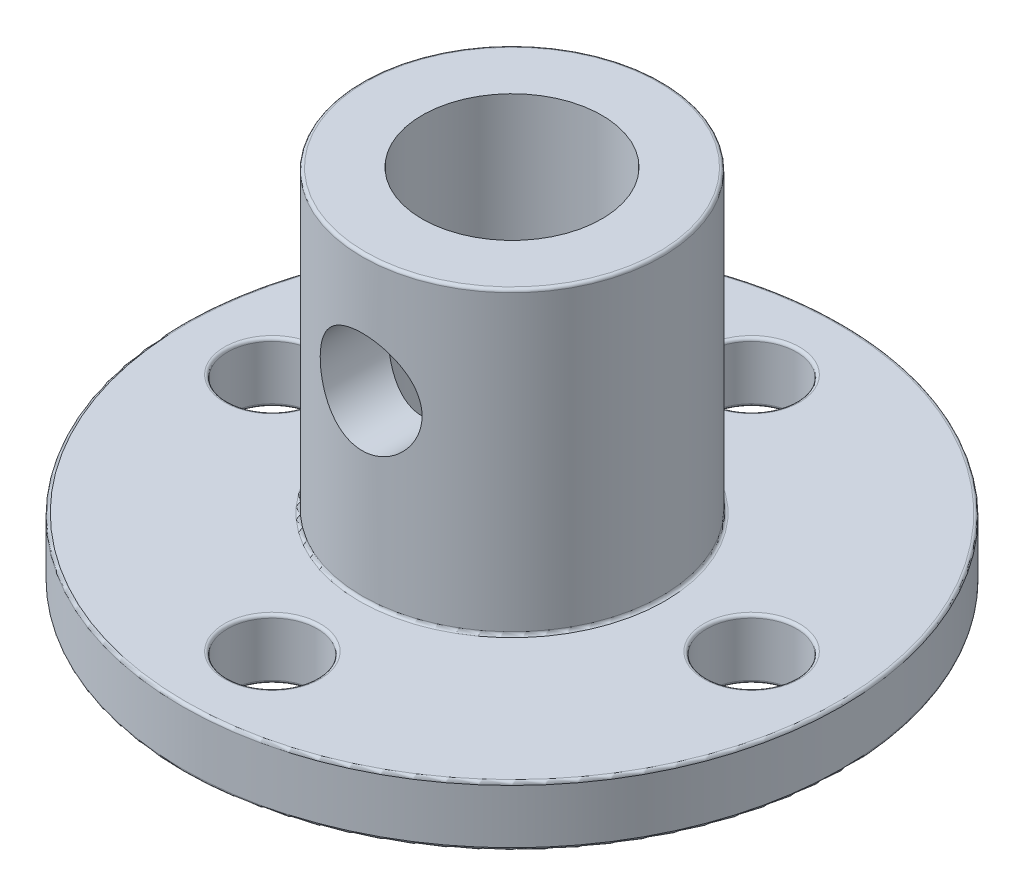
SolidWorks part; units mm, degrees
ref_plane "Front Plane" through (0, 0, 0) normal (0, 0, 1) x (1, 0, 0)
ref_plane "Top Plane" through (0, 0, 0) normal (0, 1, 0) x (1, 0, 0)
ref_plane "Right Plane" through (0, 0, 0) normal (1, 0, 0) x (0, 0, -1)
sketch "Sketch2" plane through (0, 0, 0) normal (0, 1, 0) x (1, 0, 0)
  circle A0 centre (0, 0) radius 11
  dimension "D1" = 22
extrude "Boss-Extrude1" add sketch "Sketch2" along normal blind 2
sketch "Sketch3" plane through (0, 2, 0) normal (0, 1, 0) x (1, 0, 0)
  circle A0 centre (0, 0) radius 5
  dimension "D1" = 10
extrude "Boss-Extrude2" add sketch "Sketch3" along normal blind 10
sketch "Sketch4" plane through (0, 12, 0) normal (0, 1, 0) x (1, 0, 0)
  circle A0 centre (0, 0) radius 3
  dimension "D1" = 6
extrude "Cut-Extrude1" cut sketch "Sketch4" against normal through all
sketch "Sketch5" plane through (0, 2, 0) normal (0, 1, 0) x (1, 0, 0)
  circle A0 centre (0, 0) radius 8 construction
  circle A1 centre (0, -8) radius 1.5
  circle A2 centre (-8, 0) radius 1.5
  circle A3 centre (0, 8) radius 1.5
  circle A4 centre (8, 0) radius 1.5
  point P14 (0, 0)
  dimension "D1" = 16
  dimension "D2" = 3
extrude "Cut-Extrude2" cut sketch "Sketch5" against normal through all
fillet "Fillet1" radius 0.1 12 edges at (0, 0, 11) (0, 2, 5) (0, 2, 11) (0, 12, 5) (0, 2, -6.5) (0, 0, -6.5) (8, 2, 1.5) (8, 0, 1.5) (0, 2, 9.5) (0, 0, 9.5) (-8, 2, 1.5) (-8, 0, 1.5)
ref_plane "Plane1" through (0, 0, 5) normal (0, 0, 1) x (1, 0, 0)
sketch "Sketch9" plane through (0, 0, 5) normal (0, 0, 1) x (1, 0, 0)
  line L0 (0, 0) -> (0, 8) construction
  dimension "D1" = 8
hole_wizard "M3 Clearance Hole1" positions "Sketch10" profile "Sketch11" hole size "M3" standard "ANSI Metric"
sketch "Sketch10" plane through (0, 0, 5) normal (0, 0, 1) x (1, 0, 0)
  point P0 (0, 8)
sketch "Sketch11" plane through (0, 8, 5) normal (1, 0, 0) x (0, -1, 0)
  line L0 (0, 0) -> (0, 2)
  line L1 (0, 2) -> (1.7, 2)
  line L2 (1.7, 2) -> (1.7, 0)
  line L5 (1.7, 0) -> (0, 0)
  line L11 (0, -6.35) -> (0, 107.95) construction
  dimension "Thru Hole Dia." = 3.4
  dimension "Thru Hole Depth" = 2
